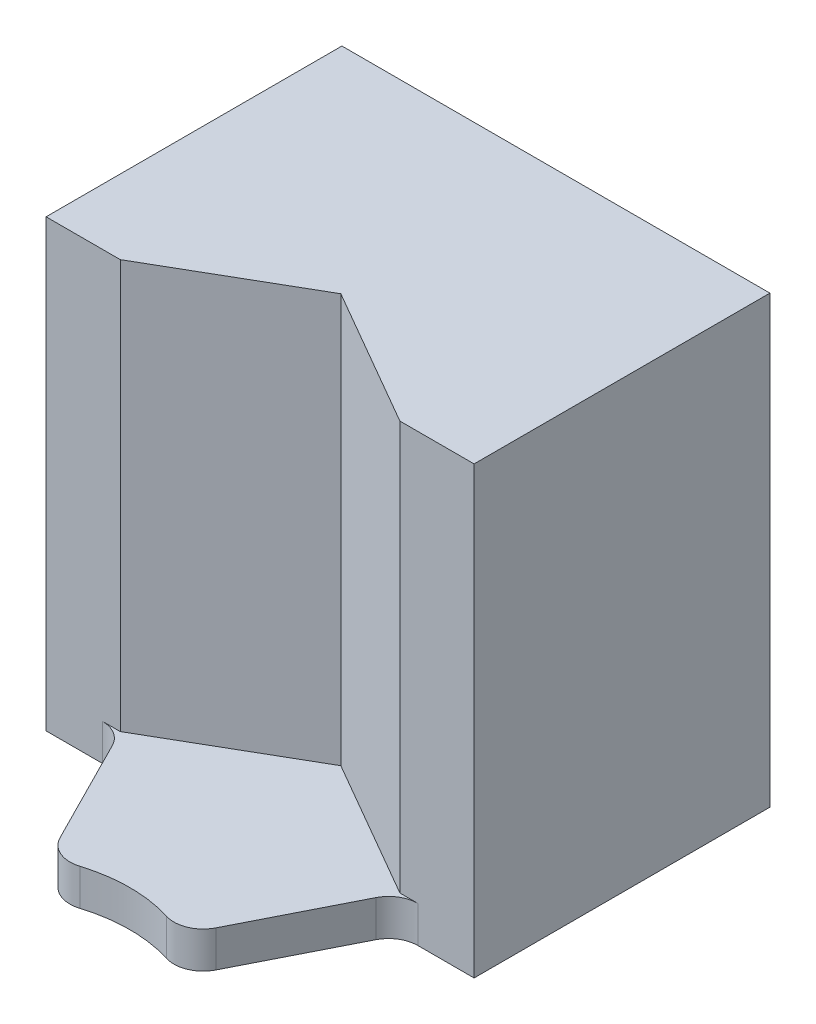
SolidWorks part; units mm, degrees
ref_plane "Front Plane" through (0, 0, 0) normal (0, 0, 1) x (1, 0, 0)
ref_plane "Top Plane" through (0, 0, 0) normal (0, 1, 0) x (1, 0, 0)
ref_plane "Right Plane" through (0, 0, 0) normal (1, 0, 0) x (0, 0, -1)
sketch "Sketch1" plane through (0, 0, 0) normal (0, 1, 0) x (1, 0, 0)
  line L0 (0, 0) -> (47.8912, -27.65)
  line L1 (47.8912, -27.65) -> (73.3, -27.65)
  line L2 (73.3, -27.65) -> (73.3, 73.6729)
  line L3 (73.3, 73.6729) -> (-73.3, 73.6729)
  line L4 (-73.3, 73.6729) -> (-73.3, -27.65)
  line L5 (-73.3, -27.65) -> (-47.8912, -27.65)
  line L6 (-47.8912, -27.65) -> (0, 0)
  line L7 (-18.9998, 73.6729) -> (19, 73.6729) construction
  line L8 (0, 0) -> (-30, -17.3205) construction
  line L9 (-30, -17.3205) -> (-30, -51.9615) construction
  line L10 (-30, -51.9615) -> (0, -69.282) construction
  line L11 (0, -69.282) -> (30, -51.9615) construction
  line L12 (30, -51.9615) -> (30, -17.3205) construction
  line L13 (30, -17.3205) -> (0, 0) construction
  circle A0 centre (0, -34.641) radius 30 construction
  point P9 (0, 0)
  point P16 (0, 0)
  dimension "D4" = 60
  dimension "D2" = 55.3
  dimension "D3" = 146.6
extrude "Boss-Extrude1" add sketch "Sketch1" along normal blind 140
sketch "Sketch3" plane through (0, 0, 0) normal (0, -1, 0) x (1, 0, 0)
  line L0 (-47.8912, 27.65) -> (-22.5815, 77.65)
  line L1 (22.5815, 77.65) -> (47.8912, 27.65)
  line L15 (-47.8912, 27.65) -> (-73.3, 27.65)
  line L16 (-73.3, 27.65) -> (-73.3, -73.6729)
  line L17 (-73.3, -73.6729) -> (73.3, -73.6729)
  line L18 (73.3, -73.6729) -> (73.3, 27.65)
  line L19 (73.3, 27.65) -> (47.8912, 27.65)
  arc A0 (-22.5815, 77.65) -> (22.5815, 77.65) centre (0, 122.2603) ccw
  point P0 (47.8912, 27.65)
  point P8 (0, 0)
  dimension "D3" = 50
  dimension "D2" = 50
extrude "Boss-Extrude2" add sketch "Sketch3" along normal blind 12.5
fillet "Fillet1" radius 10 4 edges at (47.8912, -6.25, 27.65) (22.5815, -6.25, 77.65) (-22.5815, -6.25, 77.65) (-47.8912, -6.25, 27.65)
